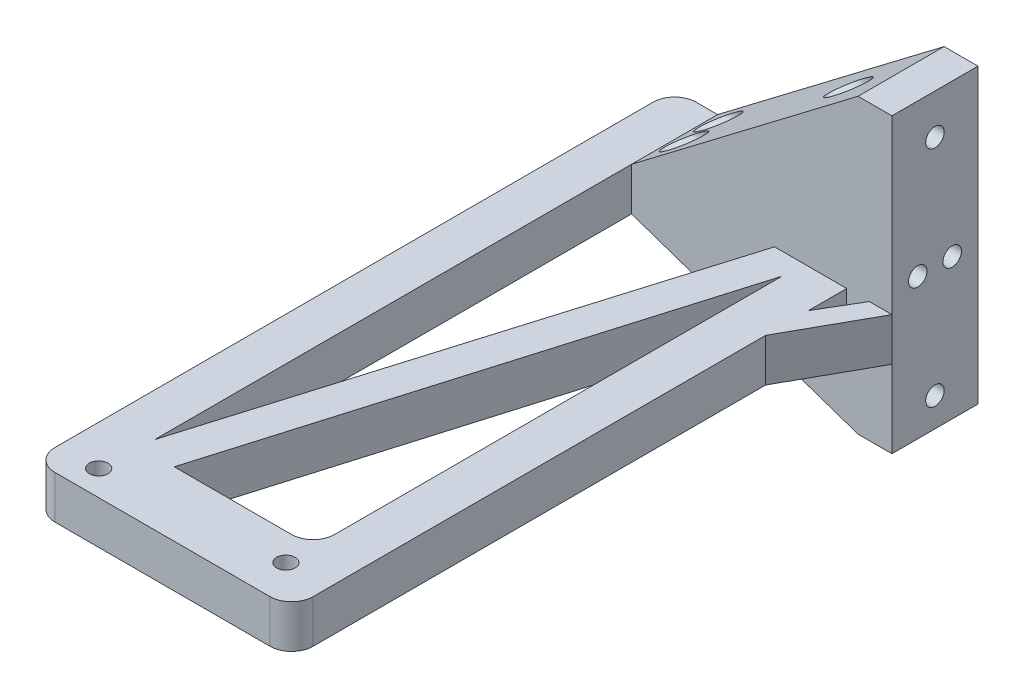
SolidWorks part; units mm, degrees
ref_plane "前视基准面" through (0, 0, 0) normal (0, 0, 1) x (1, 0, 0)
ref_plane "上视基准面" through (0, 0, 0) normal (0, 1, 0) x (1, 0, 0)
ref_plane "右视基准面" through (0, 0, 0) normal (1, 0, 0) x (0, 0, -1)
sketch "草图1" plane through (0, 0, 0) normal (0, 1, 0) x (1, 0, 0)
  line L0 (5.9312, 81.5722) -> (53.1808, 81.5722)
  line L1 (-17.3192, 81.5722) -> (5.9312, 81.5722)
  line L2 (-17.3192, 81.5722) -> (-17.3192, -67.4278)
  line L3 (-17.3192, -67.4278) -> (0.4312, -67.4278)
  line L7 (53.1808, 81.5722) -> (53.1808, 61.5722)
  line L12 (42.6808, -57.6007) -> (42.6808, -67.4278)
  line L13 (42.6808, -67.4278) -> (0.4312, -67.4278)
  line L15 (42.6808, -57.6007) -> (42.6808, 31.7573)
  line L17 (47.9308, 61.5722) -> (42.6808, 61.5722)
  line L18 (42.6808, 61.5722) -> (42.6808, 52.6895)
  line L19 (25.9063, 61.5722) -> (-7.3192, 61.5722)
  line L21 (0.4312, -52.4278) -> (32.6808, -52.4278)
  line L22 (32.6808, -52.4278) -> (32.6808, 56.5081)
  line L23 (-7.3192, 61.5722) -> (-7.3192, -49.2207)
  line L24 (25.9063, 61.5722) -> (-7.3192, -49.2207)
  line L25 (32.6808, 56.5081) -> (0.4312, -52.4278)
  line L26 (47.9308, 61.5722) -> (42.6808, 52.6895)
  line L27 (53.1808, 61.5722) -> (42.6808, 42.721)
  line L28 (42.6808, 42.721) -> (42.6808, 31.7573)
  point P0 (0, 0)
  dimension "D1" = 149
  dimension "D2" = 60
  dimension "D3" = 70.5
  dimension "D4" = 10
  dimension "D5" = 10
  dimension "D6" = 15
  dimension "D7" = 20
extrude "凸台-拉伸1" add sketch "草图1" along normal blind 10
sketch "草图4" plane through (0, 10, 0) normal (0, 1, 0) x (1, 0, 0)
  line L0 (45.3058, 81.5722) -> (45.3058, 61.5722)
  line L1 (53.1808, 81.5722) -> (-17.3192, 81.5722) construction
  line L2 (42.6808, 61.5722) -> (47.9308, 61.5722) construction
  line L3 (45.3058, 61.5722) -> (53.1808, 61.5722)
  line L4 (53.1808, 61.5722) -> (53.1808, 81.5722)
  line L5 (53.1808, 81.5722) -> (45.3058, 81.5722)
  line L7 (53.1808, 61.5722) -> (53.1808, 81.5722) construction
  point P6 (0, 0)
  point P10 (12.8492, 89.0252)
extrude "凸台-拉伸2" add sketch "草图4" along normal blind 40
sketch "草图5" plane through (45.3058, 0, 0) normal (-1, 0, 0) x (0, 0, 1)
  line L0 (-75.5722, 14.7) -> (-60.9452, 14.7) construction
  line L1 (-71.5722, 50) -> (-71.5722, 5.7819) construction
  line L2 (-81.5722, 50) -> (-61.5722, 50) construction
  line L3 (-81.5722, 10) -> (-61.5722, 10) construction
  circle A0 centre (-75.5722, 14.7) radius 2.15
  circle A1 centre (-67.5722, 14.7) radius 2.15
  circle A2 centre (-71.5722, 40.7) radius 2.15
  dimension "D2" = 4.3
  dimension "D3" = 4.3
  dimension "D5" = 4.3
  dimension "D1" = 8
  dimension "D4" = 4
  dimension "D6" = 26
  dimension "D7" = 4.7
extrude "切除-拉伸1" cut sketch "草图5" against normal up to next and the other way blind 53
sketch "草图6" plane through (0, 10, 0) normal (0, 1, 0) x (1, 0, 0)
  line L0 (32.8487, -73.9607) -> (32.6808, -58.7426) construction
  line L1 (32.6808, -52.4278) -> (32.6808, 56.5081) construction
  line L2 (-25.0369, -58.7426) -> (44.4062, -58.7426) construction
  circle A0 centre (-8.0192, -61.5426) radius 2.15
  circle A1 centre (32.6808, -58.7426) radius 2.15
  point P4 (-8.0192, -61.5426)
  dimension "D1" = 4.3
  dimension "D2" = 4.3
  dimension "D3" = 40.7
  dimension "D4" = 2.8
extrude "切除-拉伸2" cut sketch "草图6" against normal up to next
fillet "圆角1" radius 5 3 edges at (-17.3192, 5, -81.5722) (42.6808, 5, 67.4278) (-17.3192, 5, 67.4278)
fillet "圆角2" radius 5 1 edges at (32.6808, 5, 52.4278)
sketch "草图7" plane through (0, 0, 0) normal (0, -1, 0) x (1, 0, 0)
  line L0 (53.1808, -61.5722) -> (53.1808, -81.5722)
  line L1 (53.1808, -81.5722) -> (45.3058, -81.5722)
  line L2 (53.1808, -81.5722) -> (-12.3192, -81.5722) construction
  line L3 (45.3058, -81.5722) -> (45.3058, -61.5722)
  line L4 (45.3058, -61.5722) -> (53.1808, -61.5722)
  dimension "D1" = 7.875
extrude "凸台-拉伸3" add sketch "草图7" along normal blind 18
sketch "草图8" plane through (45.3058, 0, 0) normal (-1, 0, 0) x (0, 0, 1)
  line L0 (-71.5722, -18) -> (-71.5722, 20.1583) construction
  line L1 (-61.5722, -18) -> (-81.5722, -18) construction
  line L2 (-61.5722, 0) -> (-81.5722, 0) construction
  circle A0 centre (-71.5722, -11.3) radius 2.15
  dimension "D1" = 4.3
  dimension "D2" = 11.3
extrude "切除-拉伸3" cut sketch "草图8" against normal up to next
sketch "草图13" plane through (0, 0, -61.5722) normal (0, 0, 1) x (1, 0, 0)
  line L3 (45.3058, 0) -> (45.3058, -18)
  line L4 (45.3058, -18) -> (-7.3192, 0)
  line L5 (-7.3192, 0) -> (45.3058, 0)
sketch "草图14" plane through (53.1808, 0, 0) normal (1, 0, 0) x (0, 0, -1)
  circle A0 centre (71.5722, 40.7) radius 3.5
  circle A1 centre (67.5722, 14.7) radius 3.5
  circle A2 centre (75.5722, 14.7) radius 3.5
  circle A3 centre (71.5722, -11.3) radius 3.5
  dimension "D1" = 7
  dimension "D2" = 7
  dimension "D3" = 7
  dimension "D4" = 7
extrude "凸台-拉伸8" add sketch "草图13" against normal blind 20
sketch "草图15" plane through (0, 10, 0) normal (0, 1, 0) x (1, 0, 0)
  line L1 (45.3058, 81.5722) -> (-7.3192, 81.5722)
  line L2 (45.3058, 81.5722) -> (45.3058, 61.5722)
  line L3 (45.3058, 61.5722) -> (-7.3192, 61.5722)
  line L4 (-7.3192, 81.5722) -> (-7.3192, 61.5722)
extrude "凸台-拉伸9" add sketch "草图15" along normal blind 40
extrude "切除-拉伸8" cut sketch "草图14" against normal blind 54 from offset 7.875 offset against normal yes
sketch "草图17" plane through (0, 0, -61.5722) normal (0, 0, 1) x (1, 0, 0)
  line L1 (-7.3192, 50) -> (53.1808, 50) construction
  line L6 (-7.3192, 10) -> (-7.3192, 50)
  line L7 (-7.3192, 50) -> (45.3058, 50)
  line L8 (45.3058, 50) -> (-7.3192, 10)
  line L9 (53.1808, 50) -> (53.1808, 10) construction
  dimension "D1" = 7.875
extrude "切除-拉伸10" cut sketch "草图17" against normal blind 20
